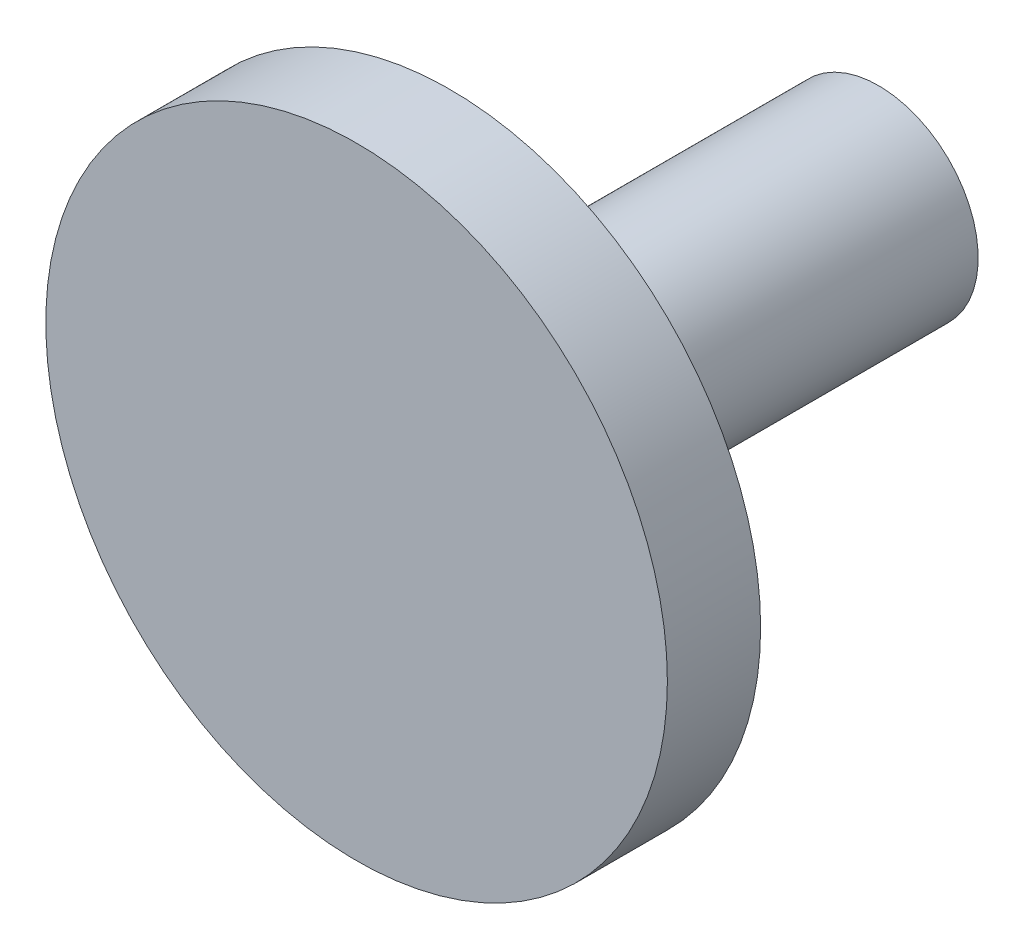
SolidWorks part; units mm, degrees
ref_plane "Plano frontal" through (0, 0, 0) normal (0, 0, 1) x (1, 0, 0)
ref_plane "Plano superior" through (0, 0, 0) normal (0, 1, 0) x (1, 0, 0)
ref_plane "Plano direito" through (0, 0, 0) normal (1, 0, 0) x (0, 0, -1)
sketch "Esboço1" plane through (0, 0, 0) normal (0, 0, 1) x (1, 0, 0)
  circle A0 centre (0, 0) radius 1.6
  dimension "D1" = 3.2
extrude "Ressalto-extrusão1" add sketch "Esboço1" along normal blind 6.9
sketch "Esboço3" plane through (0, 0, 6.9) normal (0, 0, 1) x (1, 0, 0)
  circle A0 centre (0, 0) radius 5
  dimension "D1" = 10
extrude "Ressalto-extrusão2" add sketch "Esboço3" along normal blind 1.5
